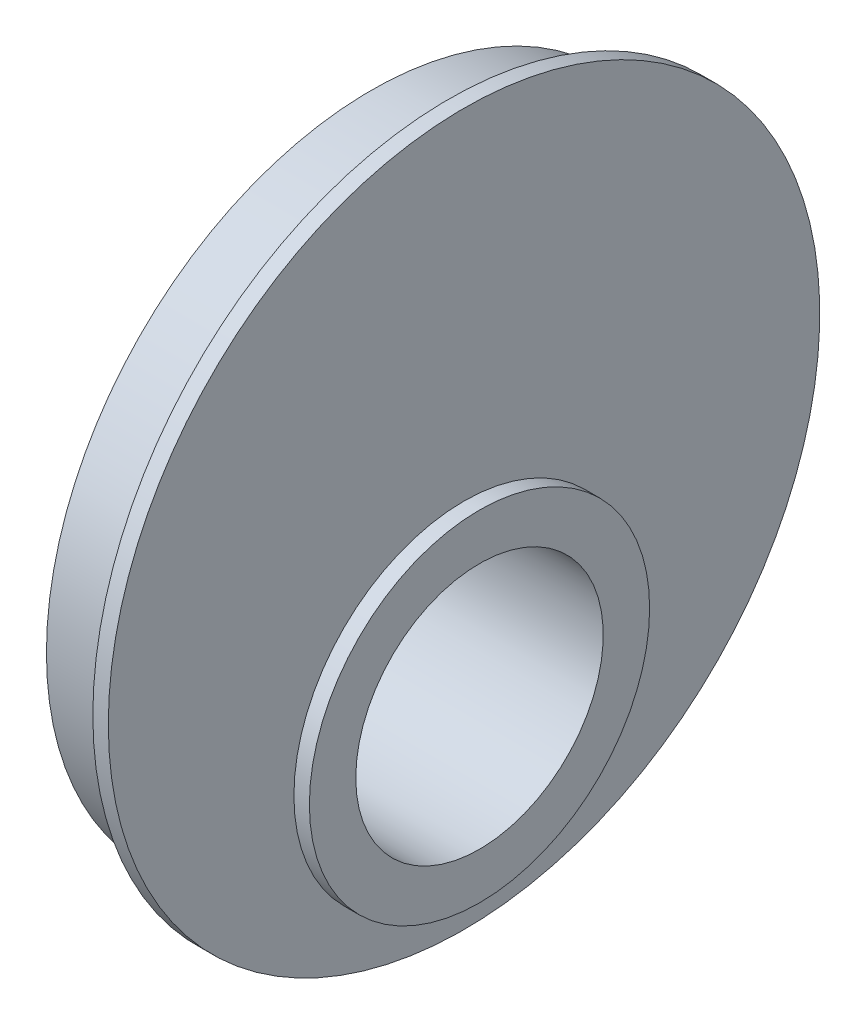
SolidWorks part; units mm, degrees
ref_plane "Front Plane" through (0, 0, 0) normal (0, 0, 1) x (1, 0, 0)
ref_plane "Top Plane" through (0, 0, 0) normal (0, 1, 0) x (1, 0, 0)
ref_plane "Right Plane" through (0, 0, 0) normal (1, 0, 0) x (0, 0, -1)
sketch "Sketch1" plane through (0, 0, 0) normal (0, 0, 1) x (1, 0, 0)
  line L0 (0, 0) -> (7753.7604, 0) construction
  line L1 (0, 0) -> (0, 21)
  line L2 (0, 21) -> (5, 21)
  line L3 (5, 21) -> (5, 23)
  line L4 (5, 23) -> (6, 23)
  line L5 (6, 23) -> (6, 0)
  line L6 (6, 0) -> (0, 0)
  point P9 (3.7661, 23)
  dimension "D1" = 46
  dimension "D2" = 42
  dimension "D3" = 6
  dimension "D4" = 1
revolve "Revolve1" add sketch "Sketch1" angle 360 about L0
sketch "Sketch2" plane through (6, 0, 0) normal (1, 0, 0) x (0, 0, -1)
  line L0 (0, 0) -> (0, -26.2822) construction
  circle A0 centre (0, -10) radius 11
  dimension "D1" = 10
  dimension "D2" = 22
extrude "Boss-Extrude1" add sketch "Sketch2" along normal blind 1
sketch "Sketch3" plane through (0, 0, 0) normal (-1, 0, 0) x (0, 0, 1)
  line L0 (0, 0) -> (0, -23) construction
  circle A0 centre (0, 0) radius 23 construction
  circle A1 centre (0, -10) radius 11
  circle A2 centre (0, -10) radius 8
  dimension "D1" = 10
  dimension "D2" = 22
  dimension "D3" = 16
extrude "Boss-Extrude2" add sketch "Sketch3" along normal blind 8
sketch "Sketch4" plane through (0, 0, 0) normal (-1, 0, 0) x (0, 0, 1)
  circle A0 centre (0, -10) radius 8
extrude "Cut-Extrude1" cut sketch "Sketch4" against normal through all
sketch "Sketch5" plane through (0, 0, 0) normal (0, 0, 1) x (1, 0, 0)
  line L0 (-4, -21) -> (-4, 3.6078) construction
  line L1 (-8, -21) -> (0, -21) construction
  line L2 (-4, -16.5848) -> (-5.5, -16.5848)
  line L3 (-5.5, -16.5848) -> (-5.5, -22.8003)
  line L4 (-5.5, -22.8003) -> (-4, -22.8003)
  line L5 (-4, -22.8003) -> (-4, -16.5848)
  dimension "D1" = 1.5
revolve "Cut-Revolve3" cut sketch "Sketch5" angle 360 about L0
pattern_circular "CirPattern1" count 3 over 360 about axis through (-8, -10, 0) along (1, 0, 0) of "Cut-Revolve3"
